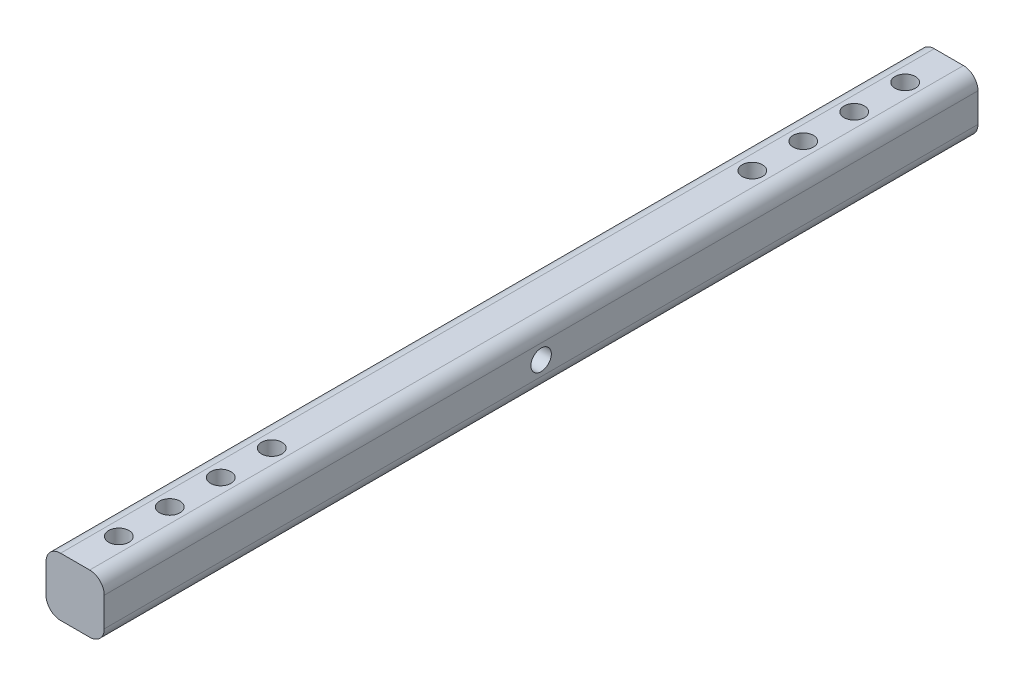
SolidWorks part; units mm, degrees
ref_plane "前视基准面" through (0, 0, 0) normal (0, 0, 1) x (1, 0, 0)
ref_plane "上视基准面" through (0, 0, 0) normal (0, 1, 0) x (1, 0, 0)
ref_plane "右视基准面" through (0, 0, 0) normal (1, 0, 0) x (0, 0, -1)
sketch "草图1" plane through (0, 0, 0) normal (0, 0, 1) x (1, 0, 0)
  line L1 (-2, -4) -> (2, -4)
  line L2 (-4, -2) -> (-4, 2)
  line L3 (-2, 4) -> (2, 4)
  line L4 (4, -2) -> (4, 2)
  line L5 (-4, -4) -> (4, 4) construction
  line L6 (-4, 4) -> (4, -4) construction
  arc A0 (2, -4) -> (4, -2) centre (2, -2) ccw
  arc A1 (-4, 2) -> (-2, 4) centre (-2, 2) cw
  arc A2 (-2, -4) -> (-4, -2) centre (-2, -2) cw
  arc A3 (2, 4) -> (4, 2) centre (2, 2) cw
  point P0 (0, 0)
  dimension "D3" = 2
  dimension "D1" = 8
  dimension "D2" = 8
extrude "凸台-拉伸1" add sketch "草图1" along normal mid plane 120
sketch "草图2" plane through (4, 0, 0) normal (1, 0, 0) x (0, 0, -1)
  circle A0 centre (0, 0) radius 1.4
  dimension "D1" = 2.8
extrude "切除-拉伸1" cut sketch "草图2" against normal through all
sketch "草图3" plane through (0, 4, 0) normal (0, 1, 0) x (1, 0, 0)
  circle A0 centre (0, -54) radius 1.4
  dimension "D1" = 2.8
  dimension "D2" = 54
extrude "切除-拉伸2" cut sketch "草图3" against normal through all
mirror "镜向1" about plane through (0, 0, 0) normal (0, 0, 1) of "切除-拉伸2"
pattern_linear "阵列(线性)1" count 4 spacing 7 along (0, 0, 1) of "镜向1", "切除-拉伸2"
mirror "镜向2" about plane through (0, 0, 0) normal (0, 0, 1) of "阵列(线性)1"
sketch "草图4" plane through (0, 4, 0) normal (0, 1, 0) x (1, 0, 0)
  line L0 (-0.9798, -60) -> (0.9798, -60)
  arc A0 (0.9798, -60) -> (-0.9798, -60) centre (0, -61) ccw construction
  arc A1 (0.9798, -60) -> (-0.9798, -60) centre (0, -61) ccw
extrude "凸台-拉伸2" add sketch "草图4" against normal up to surface (8 mm away) up to face at (0, -4, 0)
sketch "草图5" plane through (0, -4, 0) normal (0, -1, 0) x (1, 0, 0)
  line L0 (-0.9798, -60) -> (0.9798, -60)
  arc A0 (0.9798, -60) -> (-0.9798, -60) centre (0, -61) ccw construction
  arc A1 (0.9798, -60) -> (-0.9798, -60) centre (0, -61) ccw
extrude "凸台-拉伸3" add sketch "草图5" against normal up to surface (8 mm away) up to face at (0, 4, -19.9333)
